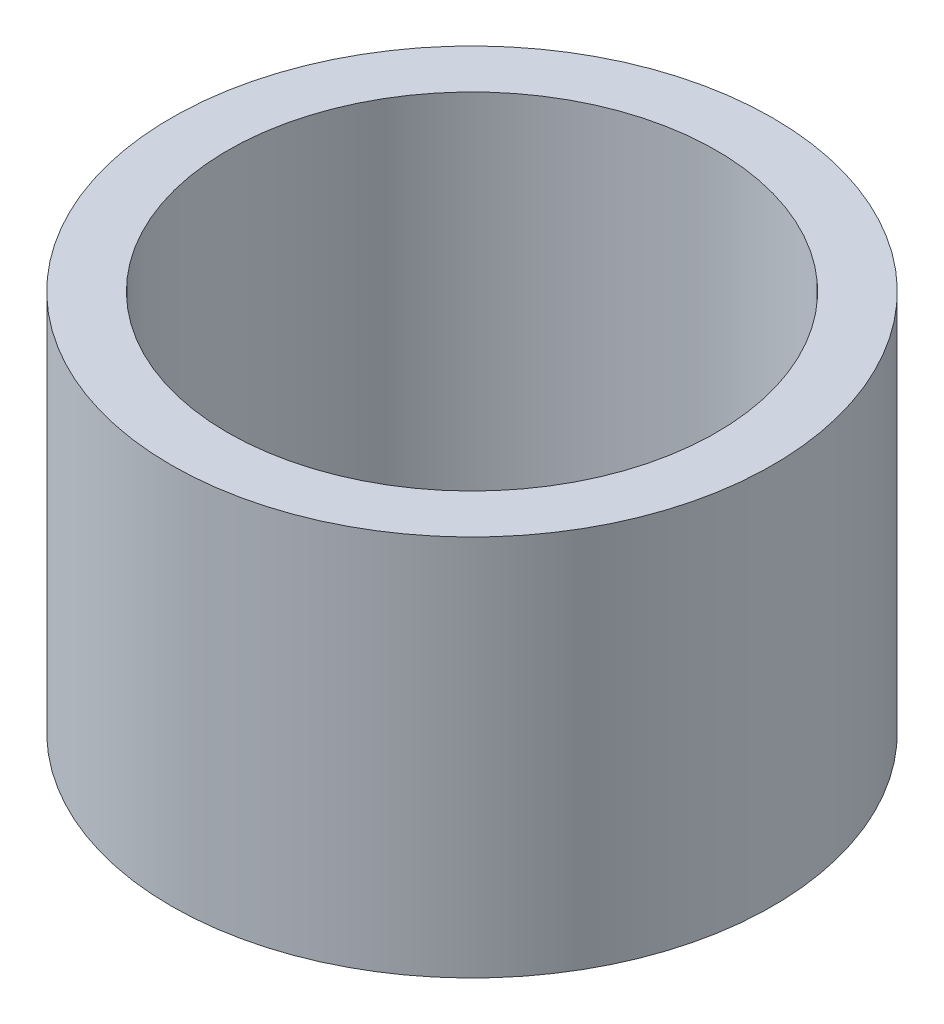
SolidWorks part; units mm, degrees
ref_plane "Front Plane" through (0, 0, 0) normal (0, 0, 1) x (1, 0, 0)
ref_plane "Top Plane" through (0, 0, 0) normal (0, 1, 0) x (1, 0, 0)
ref_plane "Right Plane" through (0, 0, 0) normal (1, 0, 0) x (0, 0, -1)
sketch "Sketch1" plane through (0, 0, 0) normal (0, 1, 0) x (1, 0, 0)
  circle A0 centre (0, 0) radius 4.0635
  circle A1 centre (0, 0) radius 5
  dimension "D1" = 8.127
  dimension "D2" = 10
extrude "Boss-Extrude1" add sketch "Sketch1" along normal mid plane 6.35
